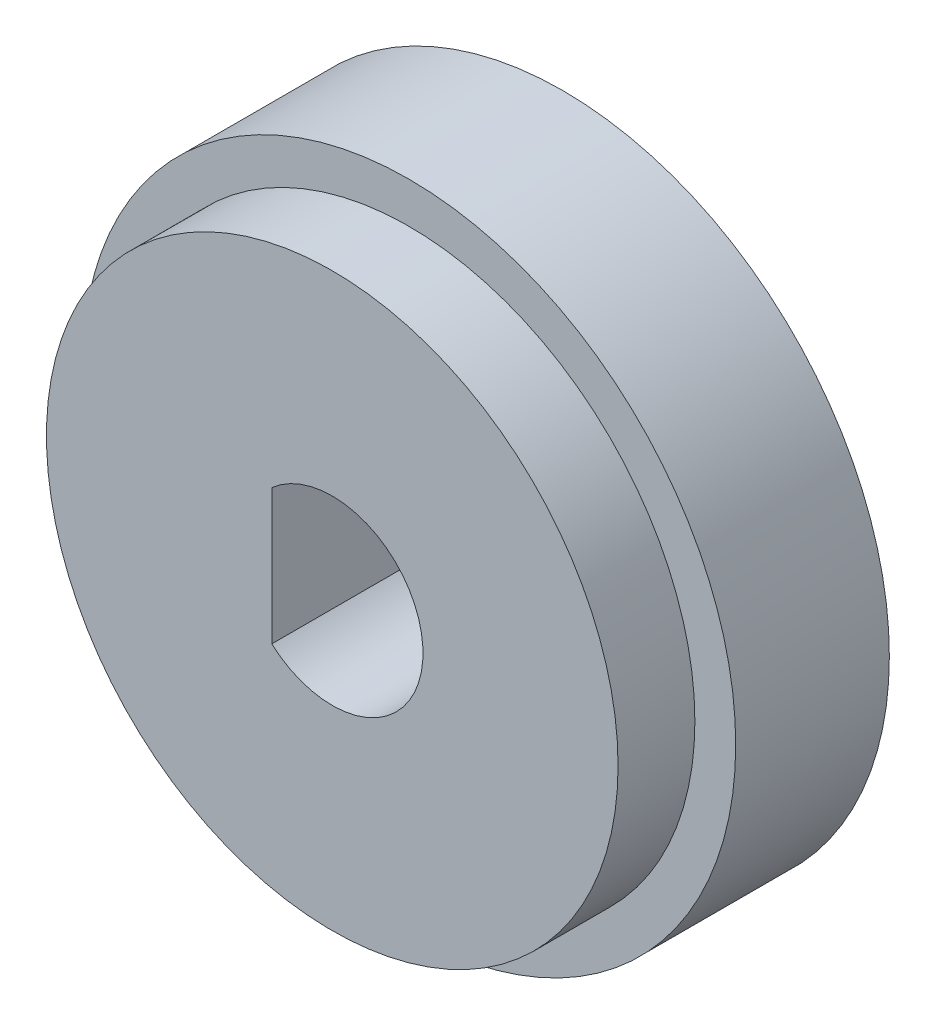
SolidWorks part; units mm, degrees
ref_plane "Front Plane" through (0, 0, 0) normal (0, 0, 1) x (1, 0, 0)
ref_plane "Top Plane" through (0, 0, 0) normal (0, 1, 0) x (1, 0, 0)
ref_plane "Right Plane" through (0, 0, 0) normal (1, 0, 0) x (0, 0, -1)
sketch "Sketch1" plane through (0, 0, 0) normal (0, 0, 1) x (1, 0, 0)
  circle A0 centre (0, 0) radius 10.8
  dimension "D1" = 21.6
extrude "Boss-Extrude1" add sketch "Sketch1" along normal blind 5.08
sketch "Sketch2" plane through (0, 0, 5.08) normal (0, 0, 1) x (1, 0, 0)
  circle A0 centre (0, 0) radius 9.45
  dimension "D1" = 18.9
extrude "Boss-Extrude2" add sketch "Sketch2" along normal blind 2.54
sketch "Sketch3" plane through (0, 0, 7.62) normal (0, 0, 1) x (1, 0, 0)
  line L1 (-2, 0) -> (-2, 2.2361)
  line L2 (-2, 0) -> (-2, -2.2361)
  arc A0 (-2, -2.2361) -> (-2, 2.2361) centre (0, 0) ccw
  dimension "D1" = 6
extrude "Cut-Extrude1" cut sketch "Sketch3" against normal through all
